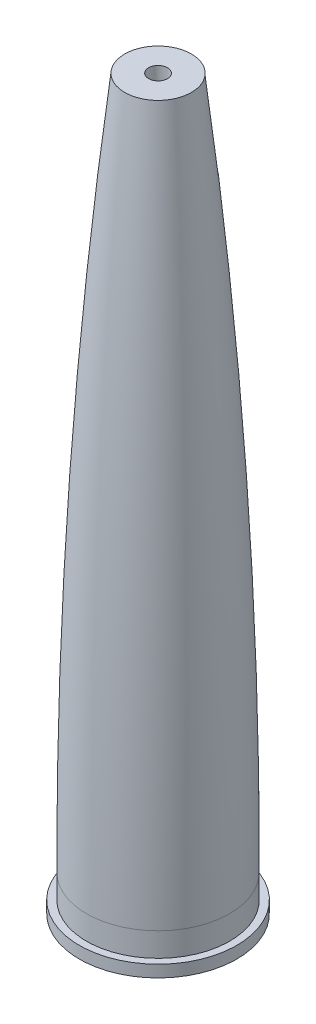
SolidWorks part; units mm, degrees
material "Nylon 101"
ref_plane "Front" through (0, 0, 0) normal (0, 0, 1) x (1, 0, 0)
ref_plane "Top" through (0, 0, 0) normal (0, 1, 0) x (1, 0, 0)
ref_plane "Right" through (0, 0, 0) normal (1, 0, 0) x (0, 0, -1)
sketch "Sketch1" plane through (0, 0, 0) normal (0, 0, 1) x (1, 0, 0)
  line L0 (-10.0812, -305.2623) -> (-10.0812, 226.5101) construction
  line L1 (-83.82, -305.2623) -> (-10.0812, -305.2623)
  line L2 (-83.82, -305.2623) -> (-83.82, -292.5623)
  line L3 (-83.82, -292.5623) -> (-76.2, -292.5623)
  line L4 (-76.2, -292.5623) -> (-76.2, -267.1623)
  line L5 (-35.4812, 469.4377) -> (-10.0812, 469.4377)
  line L6 (-10.0812, 469.4377) -> (-10.0812, -305.2623)
  line L7 (0, 0) -> (0, 15.3886) construction
  arc A0 (-35.4812, 469.4377) -> (-76.2, -267.1623) centre (6411.8653, -256.3931) ccw
  dimension "D1" = 12.7
  dimension "D2" = 7.62
  dimension "D3" = 25.4
  dimension "D4" = 762
  dimension "D5" = 76.2
  dimension "D6" = 25.4
revolve "Revolve-Thin1" add sketch "Sketch1" angle 360 about L7 wall 2.54
